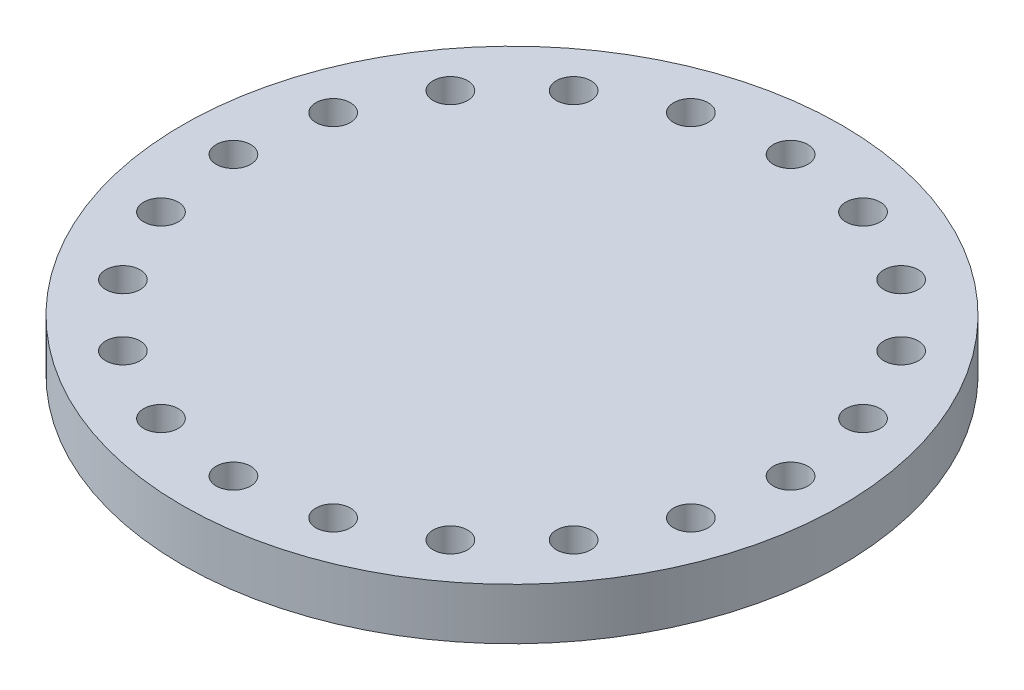
SolidWorks part; units mm, degrees
ref_plane "Front Plane" through (0, 0, 0) normal (0, 0, 1) x (1, 0, 0)
ref_plane "Top Plane" through (0, 0, 0) normal (0, 1, 0) x (1, 0, 0)
ref_plane "Right Plane" through (0, 0, 0) normal (1, 0, 0) x (0, 0, -1)
sketch "Sketch1" plane through (0, 0, 0) normal (0, 1, 0) x (1, 0, 0)
  circle A0 centre (0, 0) radius 27.05 construction
  circle A6 centre (0, -27.05) radius 1.675
  circle A21 centre (0, 0) radius 32
  circle A22 centre (-8.3589, -25.7261) radius 1.675
  circle A23 centre (-15.8996, -21.8839) radius 1.675
  circle A24 centre (-21.8839, -15.8996) radius 1.675
  circle A25 centre (-25.7261, -8.3589) radius 1.675
  circle A26 centre (-27.05, 0) radius 1.675
  circle A27 centre (-25.7261, 8.3589) radius 1.675
  circle A28 centre (-21.8839, 15.8996) radius 1.675
  circle A29 centre (-15.8996, 21.8839) radius 1.675
  circle A30 centre (-8.3589, 25.7261) radius 1.675
  circle A31 centre (0, 27.05) radius 1.675
  circle A32 centre (8.3589, 25.7261) radius 1.675
  circle A33 centre (15.8996, 21.8839) radius 1.675
  circle A34 centre (21.8839, 15.8996) radius 1.675
  circle A35 centre (25.7261, 8.3589) radius 1.675
  circle A36 centre (27.05, 0) radius 1.675
  circle A37 centre (25.7261, -8.3589) radius 1.675
  circle A38 centre (21.8839, -15.8996) radius 1.675
  circle A39 centre (15.8996, -21.8839) radius 1.675
  circle A40 centre (8.3589, -25.7261) radius 1.675
  dimension "D1" = 64
  dimension "D2" = 54.1
  dimension "D3" = 3.35
  dimension "D4" = 20
extrude "Boss-Extrude1" add sketch "Sketch1" along normal blind 5
